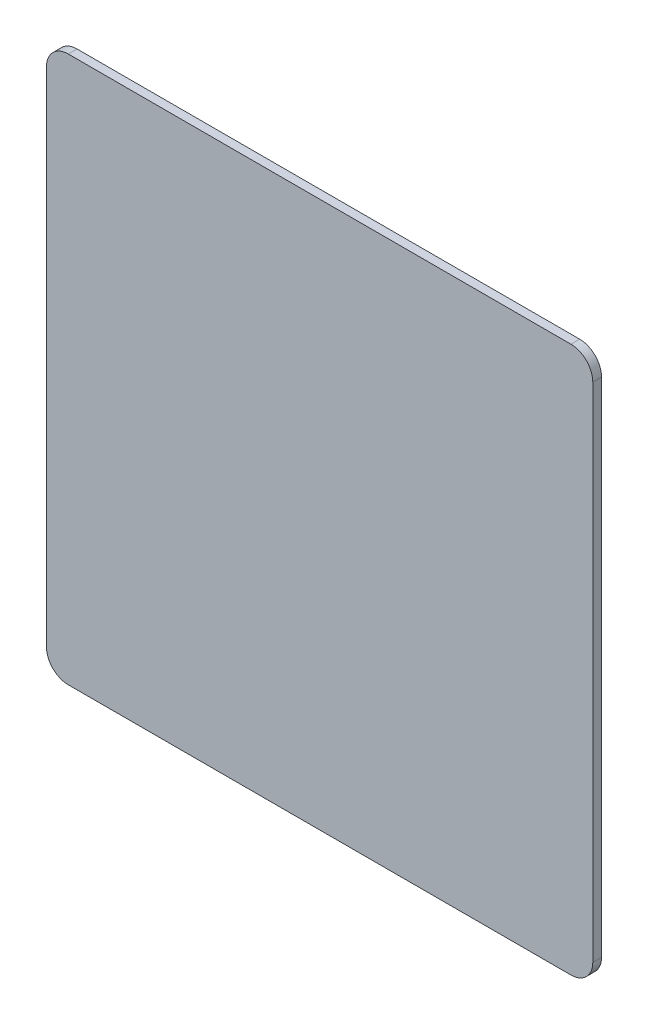
SolidWorks part; units mm, degrees
ref_plane "Front Plane" through (0, 0, 0) normal (0, 0, 1) x (1, 0, 0)
ref_plane "Top Plane" through (0, 0, 0) normal (0, 1, 0) x (1, 0, 0)
ref_plane "Right Plane" through (0, 0, 0) normal (1, 0, 0) x (0, 0, -1)
sketch "Sketch1" plane through (0, 0, 0) normal (0, 0, 1) x (1, 0, 0)
  line L1 (0, 0) -> (250, 0)
  line L2 (0, 0) -> (0, -250)
  line L3 (0, -250) -> (250, -250)
  line L4 (250, 0) -> (250, -250)
  dimension "D1" = 250
  dimension "D2" = 250
extrude "Boss-Extrude1" add sketch "Sketch1" along normal blind 4
fillet "Fillet1" radius 10 4 edges at (250, -250, 2) (0, -250, 2) (250, 0, 2) (0, 0, 2)
